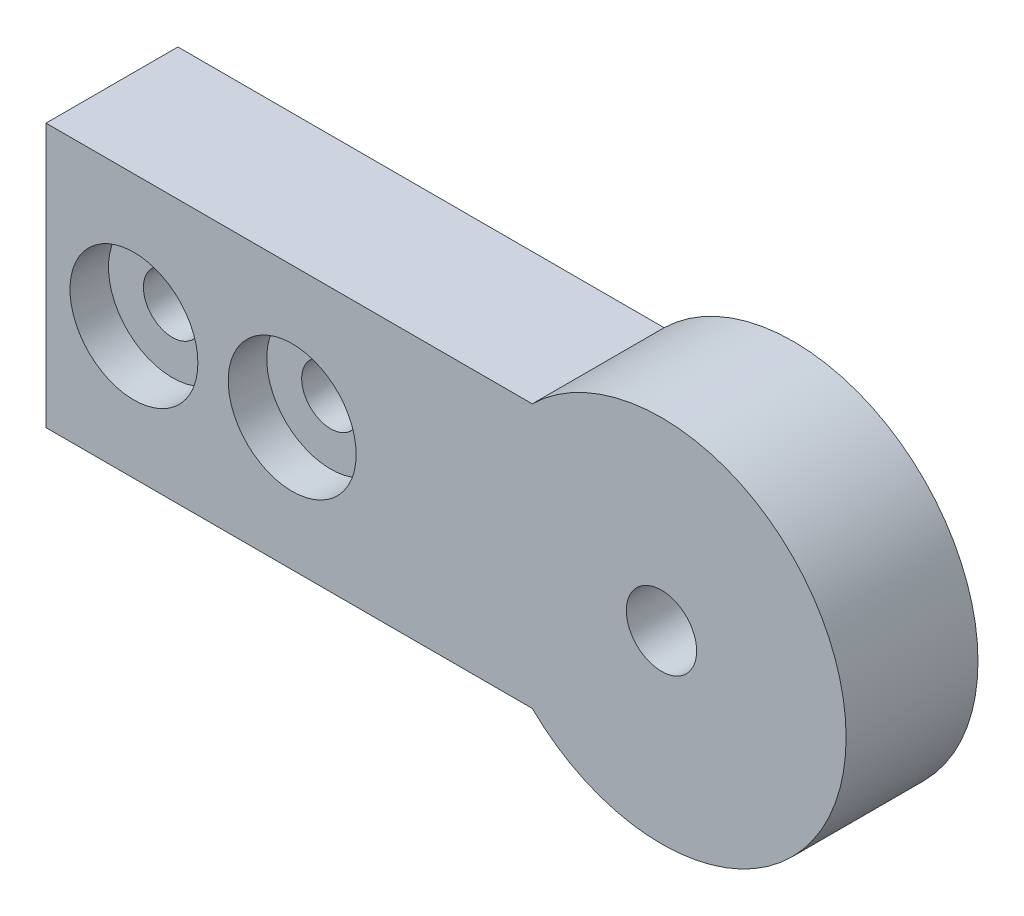
SolidWorks part; units mm, degrees
ref_plane "Front Plane" through (0, 0, 0) normal (0, 0, 1) x (1, 0, 0)
ref_plane "Top Plane" through (0, 0, 0) normal (0, 1, 0) x (1, 0, 0)
ref_plane "Right Plane" through (0, 0, 0) normal (1, 0, 0) x (0, 0, -1)
sketch "Sketch1" plane through (0, 0, 0) normal (0, 0, 1) x (1, 0, 0)
  line L1 (-14.6969, 15) -> (-70, 15)
  line L3 (-14.6969, -15) -> (-70, -15)
  line L4 (-70, 15) -> (-70, -15)
  arc A0 (-14.6969, -15) -> (-14.6969, 15) centre (0, 0) ccw
  point P7 (-19.4068, 15)
  point P8 (0, 0)
  point P9 (0, 0)
  dimension "D1" = 42
  dimension "D2" = 30
  dimension "D3" = 70
  dimension "D4" = 15
extrude "Boss-Extrude1" add sketch "Sketch1" along normal blind 15
sketch "Sketch2" plane through (0, 0, 15) normal (0, 0, 1) x (1, 0, 0)
  line L0 (-70, 15) -> (-70, -15) construction
  line L1 (-70, -15) -> (-14.6969, -15) construction
  point P0 (-60, 0)
  point P2 (-42, 0)
  dimension "D1" = 10
  dimension "D2" = 18
  dimension "D3" = 15
  dimension "D4" = 15
hole_wizard "CBORE for M6 Hex Head Bolt1" positions "Sketch2" profile "Sketch3" counterbore size "M6" standard "ANSI Metric" end condition through all
sketch "Sketch3" plane through (-60, 0, 15) normal (1, 0, 0) x (0, -1, 0)
  line L0 (0, 0) -> (0, 15)
  line L1 (0, 15) -> (3.3, 15)
  line L3 (3.3, 15) -> (3.3, 4.38)
  line L4 (3.3, 4.38) -> (7.275, 4.38)
  line L5 (7.275, 4.38) -> (7.275, 0)
  line L7 (7.275, 0) -> (0, 0)
  line L11 (0, -6.35) -> (0, 107.95) construction
  dimension "Thru Hole Dia." = 6.6
  dimension "Thru Hole Depth" = 15
  dimension "C'Bore Dia." = 14.55
  dimension "C'Bore Depth" = 4.38
sketch "Sketch4" plane through (0, 0, 15) normal (0, 0, 1) x (1, 0, 0)
  circle A0 centre (0, 0) radius 4
  dimension "D1" = 8
extrude "Cut-Extrude1" cut sketch "Sketch4" against normal up to next
